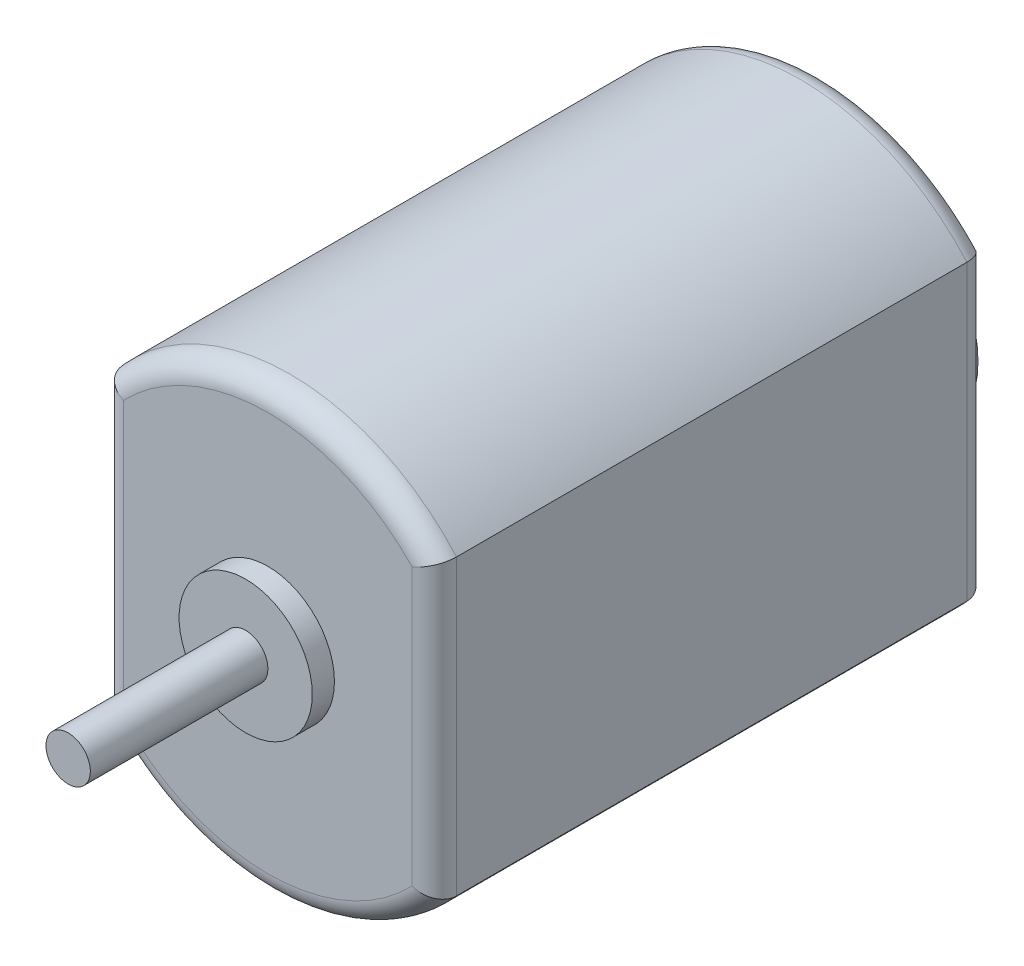
SolidWorks part; units mm, degrees
ref_plane "Top" through (0, 0, 0) normal (0, 0, 1) x (1, 0, 0)
ref_plane "Сверху" through (0, 0, 0) normal (0, 1, 0) x (1, 0, 0)
ref_plane "Справа" through (0, 0, 0) normal (1, 0, 0) x (0, 0, -1)
sketch "Sketch1" plane through (0, 0, 0) normal (0, 0, 1) x (1, 0, 0)
  line L0 (-7.5, -6.6144) -> (-7.5, 6.6144)
  line L1 (7.5, -6.6144) -> (7.5, 6.6144)
  arc A0 (-7.5, -6.6144) -> (7.5, -6.6144) centre (0, 0) ccw
  arc A1 (7.5, 6.6144) -> (-7.5, 6.6144) centre (0, 0) ccw
extrude "Boss-Extrude1" add sketch "Sketch1" along normal blind 25
sketch "Sketch2" plane through (0, 0, 25) normal (0, 0, 1) x (1, 0, 0)
  circle A0 centre (0, 0) radius 3
extrude "Boss-Extrude2" add sketch "Sketch2" along normal blind 1
sketch "Sketch3" plane through (0, 0, 26) normal (0, 0, 1) x (1, 0, 0)
  circle A0 centre (0, 0) radius 1
extrude "Boss-Extrude3" add sketch "Sketch3" along normal blind 8
sketch "Sketch4" plane through (0, 0, 0) normal (0, 0, -1) x (-1, 0, 0)
  line L0 (4, 3) -> (4, -3)
  arc A0 (4, 3) -> (4, -3) centre (0, 0) ccw
extrude "Boss-Extrude4" add sketch "Sketch4" along normal blind 2
sketch "Sketch5" plane through (0, 0, -2) normal (0, 0, -1) x (-1, 0, 0)
  circle A0 centre (0, 0) radius 1
extrude "Boss-Extrude5" add sketch "Sketch5" along normal blind 0.5 contours A0
fillet "Fillet1" radius 1 4 edges at (0, -10, 25) (7.5, 0, 25) (0, 10, 25) (-7.5, 0, 25)
fillet "Fillet2" radius 1 4 edges at (0, -10, 0) (7.5, 0, 0) (0, 10, 0) (-7.5, 0, 0)
